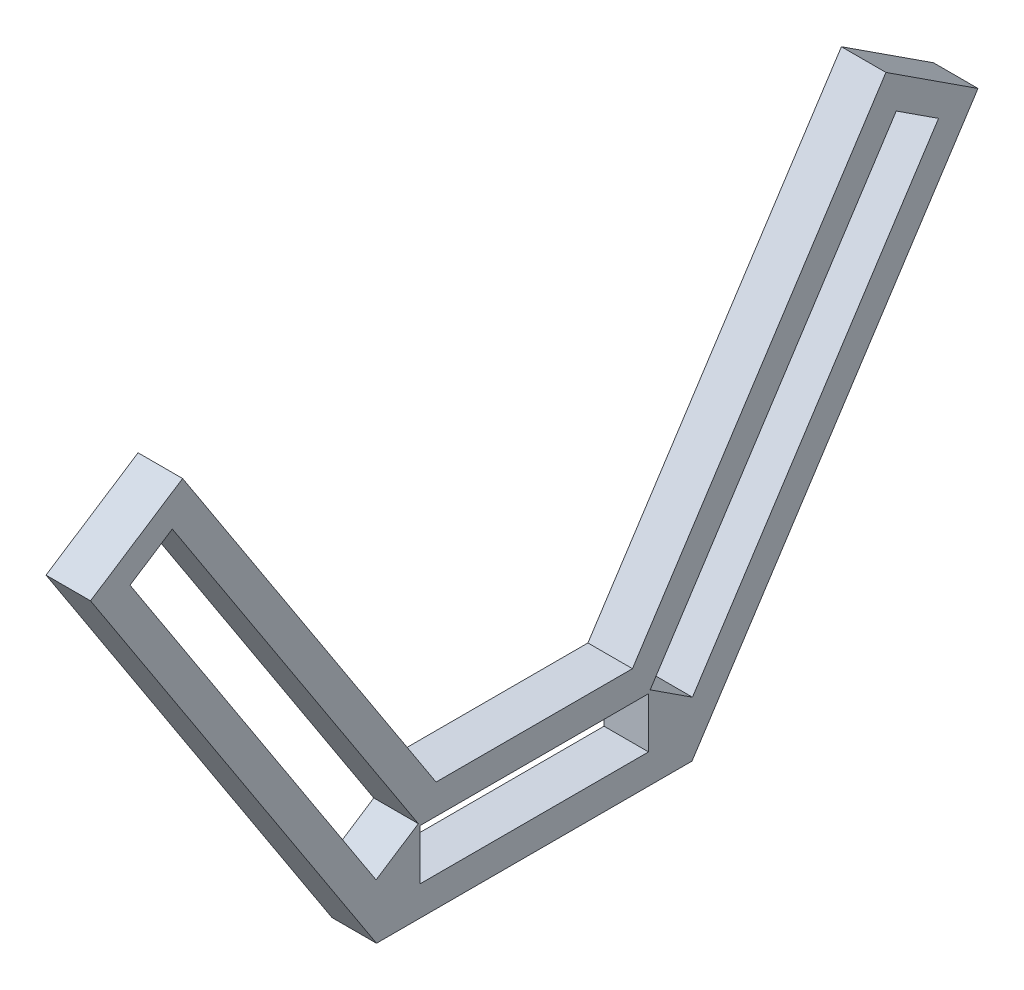
SolidWorks part; units mm, degrees
ref_plane "Front Plane" through (0, 0, 0) normal (0, 0, 1) x (1, 0, 0)
ref_plane "Top Plane" through (0, 0, 0) normal (0, 1, 0) x (1, 0, 0)
ref_plane "Right Plane" through (0, 0, 0) normal (1, 0, 0) x (0, 0, -1)
sketch "Sketch1" plane through (0, 0, 0) normal (1, 0, 0) x (0, 0, -1)
  line L0 (13.2, -2.013) -> (13.2, -5.413)
  line L7 (-13.2, -5.413) -> (13.2, -5.413)
  line L8 (-13.2, -2.013) -> (-13.2, -5.413)
  line L9 (-13.2, -2.013) -> (13.2, -2.013)
  line L10 (-13.3091, -1.8453) -> (-29.8869, 23.6367)
  line L11 (-16.159, -3.6994) -> (-32.7369, 21.7826)
  line L13 (-16.05, -3.8671) -> (-35.7681, 26.442) construction
  line L14 (3.4, 29.2932) -> (-35.7681, 26.442) construction
  line L15 (3.4, -2.013) -> (3.4, 29.2932) construction
  line L16 (0, -2.013) -> (0, 25.6367) construction
  line L17 (0, 25.6367) -> (-29.7778, 23.4691) construction
  line L18 (-29.192, 26.2362) -> (-35.3949, 22.2008)
  line L19 (-16.6358, -6.6342) -> (-35.3949, 22.2008)
  line L22 (15.2, -0.013) -> (15.2, -7.413)
  line L23 (-15.2, -7.413) -> (15.2, -7.413)
  line L25 (-12.1151, -0.013) -> (15.2, -0.013)
  line L26 (-12.1151, -0.013) -> (-29.192, 26.2362)
  line L27 (-15.2, -0.013) -> (15.2, -0.013) construction
  line L28 (-15.2, -0.013) -> (-15.2, -7.413) construction
  line L30 (-10.4329, -2.5988) -> (-29.192, 26.2362) construction
  line L31 (-16.6358, -6.6342) -> (-10.4329, -2.5988) construction
  line L34 (-16.159, -3.6994) -> (-13.3091, -1.8453)
  line L35 (-15.9914, -3.5904) -> (-32.3511, 21.5564) construction
  line L36 (-13.4767, -1.9544) -> (-29.8364, 23.1924) construction
  line L37 (-16.05, -3.8671) -> (-13.2, -2.013) construction
  line L38 (-15.9914, -3.5904) -> (-13.4767, -1.9544) construction
  line L39 (-29.8869, 23.6367) -> (-32.7369, 21.7826)
  line L40 (-16.05, -3.8671) -> (-32.6278, 21.615) construction
  line L41 (-13.2, -2.013) -> (-29.7778, 23.4691) construction
  line L42 (-29.8364, 23.1924) -> (-32.3511, 21.5564) construction
  line L43 (-29.7778, 23.4691) -> (-32.6278, 21.615) construction
  line L44 (-16.6358, -6.6342) -> (-16.1291, -7.413)
  line L45 (-16.1291, -7.413) -> (-15.2, -7.413)
  dimension "D1" = 123.047
  dimension "D2" = 26.4
  dimension "D3" = 3.4
  dimension "D4" = 2
  dimension "D5" = 0.2
extrude "Boss-Extrude1" add sketch "Sketch1" along normal blind 3
sketch "Sketch2" plane through (3, 0, 0) normal (1, 0, 0) x (0, 0, -1)
  line L0 (-13.2, -2.013) -> (-5.5, -2.013)
  line L1 (13.2, -2.013) -> (-13.2, -2.013) construction
  line L2 (-13.2, -2.013) -> (-13.2, -5.413) construction
  line L3 (-6.3, -0.013) -> (15.2, -0.013)
  line L4 (-5.5, -0.013) -> (-5.5, -7.413)
  line L5 (-6.3, -7.413) -> (15.2, -7.413)
  line L6 (15.2, -0.013) -> (15.2, -7.413)
  line M4 (-16.1291, -7.413) -> (15.2, -7.413)
  line M5 (15.2, -7.413) -> (15.2, -0.013)
  line M6 (15.2, -0.013) -> (-12.1151, -0.013)
  line M8 (-13.2, -2.013) -> (13.2, -2.013)
  line M9 (13.2, -2.013) -> (13.2, -5.413)
  line M10 (13.2, -5.413) -> (-13.2, -5.413)
  dimension "D1" = 7.7
extrude "Cut-Extrude1" cut sketch "Sketch2" against normal blind 3 contours L4 M6 M8 M9 M10 M4 M5
mirror "Mirror1" about plane through (0, 0, 5.5) normal (0, 0, 1) of bodies 102
